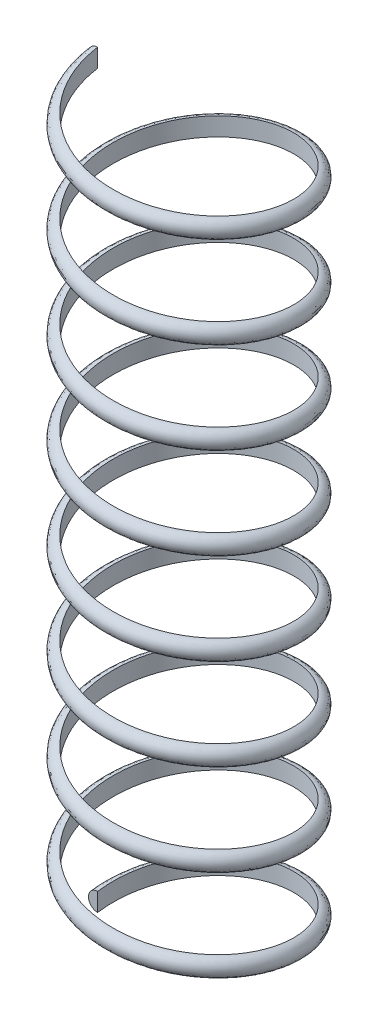
SolidWorks part; units mm, degrees
ref_plane "Front Plane" through (0, 0, 0) normal (0, 0, 1) x (1, 0, 0)
ref_plane "Top Plane" through (0, 0, 0) normal (0, 1, 0) x (1, 0, 0)
ref_plane "Right Plane" through (0, 0, 0) normal (1, 0, 0) x (0, 0, -1)
sketch "Sketch1" plane through (0, 0, 0) normal (0, 1, 0) x (1, 0, 0)
  circle A0 centre (0, 0) radius 31.75
  dimension "D1" = 63.5
curve "Helix/Spiral1" pitch 31.75 height 254 turns 8
sketch "Sketch3" plane through (0, 0, 0) normal (0, 0, 1) x (1, 0, 0)
  circle A0 centre (-31.75, 0) radius 3.175
  spline S0 degree 3 poles (-31.75, 0) (-31.75, 0.4202) (-31.0847, 1.2642) (-28.1528, 2.5272) (-23.4695, 3.7911) (-17.326, 5.0547) (-10.1047, 6.3184) (-2.2546, 7.5821) (5.7356, 8.8458) (13.3691, 10.1095) (20.1708, 11.3731) (25.7176, 12.6368) (29.6644, 13.9005) (31.7658, 15.1642) (31.8908, 16.4279) (30.0319, 17.6915) (26.3045, 18.9552) (20.9407, 20.2189) (14.2741, 21.4826) (6.7194, 22.7463) (-1.2533, 24.01) (-9.148, 25.2736) (-16.4736, 26.5373) (-22.7743, 27.801) (-27.6582, 29.0647) (-30.8213, 30.3284) (-32.067, 31.592) (-31.3176, 32.8557) (-28.6199, 34.1194) (-24.1417, 35.3831) (-18.1615, 36.6468) (-11.0514, 37.9104) (-3.2538, 39.1741) (4.7463, 40.4378) (12.451, 41.7015) (19.3812, 42.9652) (25.1056, 44.2289) (29.268, 45.4925) (31.6097, 46.7562) (31.9847, 48.0199) (30.37, 49.2836) (26.8657, 50.5473) (21.6901, 51.8109) (15.1651, 53.0746) (7.6966, 54.3383) (-0.2507, 55.602) (-8.1825, 56.8657) (-15.6051, 58.1294) (-22.057, 59.393) (-27.1365, 60.6567) (-30.5279, 61.9204) (-32.02, 63.1841) (-31.52, 64.4478) (-29.0591, 65.7114) (-24.7903, 66.9751) (-18.9792, 68.2388) (-11.9874, 69.5025) (-4.2498, 70.7662) (3.7522, 72.0299) (11.5208, 73.2935) (18.5726, 74.5572) (24.469, 75.8209) (28.843, 77.0846) (31.4227, 78.3483) (32.0474, 79.6119) (30.6784, 80.8756) (27.4007, 82.1393) (22.4184, 83.403) (16.0413, 84.6667) (8.6663, 85.9303) (0.7521, 87.194) (-7.2089, 88.4577) (-14.7214, 89.7214) (-21.318, 90.9851) (-26.5884, 92.2488) (-30.2046, 93.5124) (-31.9417, 94.7761) (-31.6916, 96.0398) (-29.4698, 97.3035) (-25.4147, 98.5672) (-19.7784, 99.8308) (-12.9116, 101.0945) (-5.2416, 102.3582) (2.7546, 103.6219) (10.5793, 104.8856) (17.7459, 106.1493) (23.8085, 107.4129) (28.3898, 108.6766) (31.205, 109.9403) (32.0787, 111.204) (30.9568, 112.4677) (27.9089, 113.7313) (23.1247, 114.995) (16.9019, 116.2587) (9.6275, 117.5224) (1.7542, 118.7861) (-6.2283, 120.0498) (-13.8233, 121.3134) (-20.5582, 122.5771) (-26.0142, 123.8408) (-29.8518, 125.1045) (-31.8322, 126.3682) (-31.8322, 127.6318) (-29.8518, 128.8955) (-26.0142, 130.1592) (-20.5582, 131.4229) (-13.8233, 132.6866) (-6.2283, 133.9502) (1.7542, 135.2139) (9.6275, 136.4776) (16.9019, 137.7413) (23.1247, 139.005) (27.9089, 140.2687) (30.9568, 141.5323) (32.0787, 142.796) (31.205, 144.0597) (28.3898, 145.3234) (23.8085, 146.5871) (17.7459, 147.8507) (10.5793, 149.1144) (2.7546, 150.3781) (-5.2416, 151.6418) (-12.9116, 152.9055) (-19.7784, 154.1692) (-25.4147, 155.4328) (-29.4698, 156.6965) (-31.6916, 157.9602) (-31.9417, 159.2239) (-30.2046, 160.4876) (-26.5884, 161.7512) (-21.318, 163.0149) (-14.7214, 164.2786) (-7.2089, 165.5423) (0.7521, 166.806) (8.6663, 168.0697) (16.0413, 169.3333) (22.4184, 170.597) (27.4007, 171.8607) (30.6784, 173.1244) (32.0474, 174.3881) (31.4227, 175.6517) (28.843, 176.9154) (24.469, 178.1791) (18.5726, 179.4428) (11.5208, 180.7065) (3.7522, 181.9701) (-4.2498, 183.2338) (-11.9874, 184.4975) (-18.9792, 185.7612) (-24.7903, 187.0249) (-29.0591, 188.2886) (-31.52, 189.5522) (-32.02, 190.8159) (-30.5279, 192.0796) (-27.1365, 193.3433) (-22.057, 194.607) (-15.6051, 195.8706) (-8.1825, 197.1343) (-0.2507, 198.398) (7.6966, 199.6617) (15.1651, 200.9254) (21.6901, 202.1891) (26.8657, 203.4527) (30.37, 204.7164) (31.9847, 205.9801) (31.6097, 207.2438) (29.268, 208.5075) (25.1056, 209.7711) (19.3812, 211.0348) (12.451, 212.2985) (4.7463, 213.5622) (-3.2538, 214.8259) (-11.0514, 216.0896) (-18.1615, 217.3532) (-24.1417, 218.6169) (-28.6199, 219.8806) (-31.3176, 221.1443) (-32.067, 222.408) (-30.8213, 223.6716) (-27.6582, 224.9353) (-22.7743, 226.199) (-16.4736, 227.4627) (-9.148, 228.7264) (-1.2533, 229.99) (6.7194, 231.2537) (14.2741, 232.5174) (20.9407, 233.7811) (26.3045, 235.0448) (30.0319, 236.3085) (31.8908, 237.5721) (31.7658, 238.8358) (29.6644, 240.0995) (25.7176, 241.3632) (20.1708, 242.6269) (13.3691, 243.8905) (5.7356, 245.1542) (-2.2546, 246.4179) (-10.1047, 247.6816) (-17.326, 248.9453) (-23.4695, 250.2089) (-28.1528, 251.4728) (-31.0847, 252.7358) (-31.75, 253.5798) (-31.75, 254) knots 0 0 0 0 0.004975 0.00995 0.014925 0.0199 0.024876 0.029851 0.034826 0.039801 0.044776 0.049751 0.054726 0.059701 0.064677 0.069652 0.074627 0.079602 0.084577 0.089552 0.094527 0.099502 0.104478 0.109453 0.114428 0.119403 0.124378 0.129353 0.134328 0.139303 0.144279 0.149254 0.154229 0.159204 0.164179 0.169154 0.174129 0.179104 0.18408 0.189055 0.19403 0.199005 0.20398 0.208955 0.21393 0.218905 0.223881 0.228856 0.233831 0.238806 0.243781 0.248756 0.253731 0.258706 0.263682 0.268657 0.273632 0.278607 0.283582 0.288557 0.293532 0.298507 0.303483 0.308458 0.313433 0.318408 0.323383 0.328358 0.333333 0.338308 0.343284 0.348259 0.353234 0.358209 0.363184 0.368159 0.373134 0.378109 0.383085 0.38806 0.393035 0.39801 0.402985 0.40796 0.412935 0.41791 0.422886 0.427861 0.432836 0.437811 0.442786 0.447761 0.452736 0.457711 0.462687 0.467662 0.472637 0.477612 0.482587 0.487562 0.492537 0.497512 0.502488 0.507463 0.512438 0.517413 0.522388 0.527363 0.532338 0.537313 0.542289 0.547264 0.552239 0.557214 0.562189 0.567164 0.572139 0.577114 0.58209 0.587065 0.59204 0.597015 0.60199 0.606965 0.61194 0.616915 0.621891 0.626866 0.631841 0.636816 0.641791 0.646766 0.651741 0.656716 0.661692 0.666667 0.671642 0.676617 0.681592 0.686567 0.691542 0.696517 0.701493 0.706468 0.711443 0.716418 0.721393 0.726368 0.731343 0.736318 0.741294 0.746269 0.751244 0.756219 0.761194 0.766169 0.771144 0.776119 0.781095 0.78607 0.791045 0.79602 0.800995 0.80597 0.810945 0.81592 0.820896 0.825871 0.830846 0.835821 0.840796 0.845771 0.850746 0.855721 0.860697 0.865672 0.870647 0.875622 0.880597 0.885572 0.890547 0.895522 0.900498 0.905473 0.910448 0.915423 0.920398 0.925373 0.930348 0.935323 0.940299 0.945274 0.950249 0.955224 0.960199 0.965174 0.970149 0.975124 0.9801 0.985075 0.99005 0.995025 1 1 1 1 construction
  dimension "D1" = 6.35
sweep "Sweep1" add profiles "Sketch3" path "Helix/Spiral1"
sketch "Sketch4" plane through (0, 0, 0) normal (0, 1, 0) x (1, 0, 0)
  circle A0 centre (0, 0) radius 31.75
  dimension "D1" = 63.5
extrude "Cut-Extrude4" cut sketch "Sketch4" along normal mid plane 558.8
